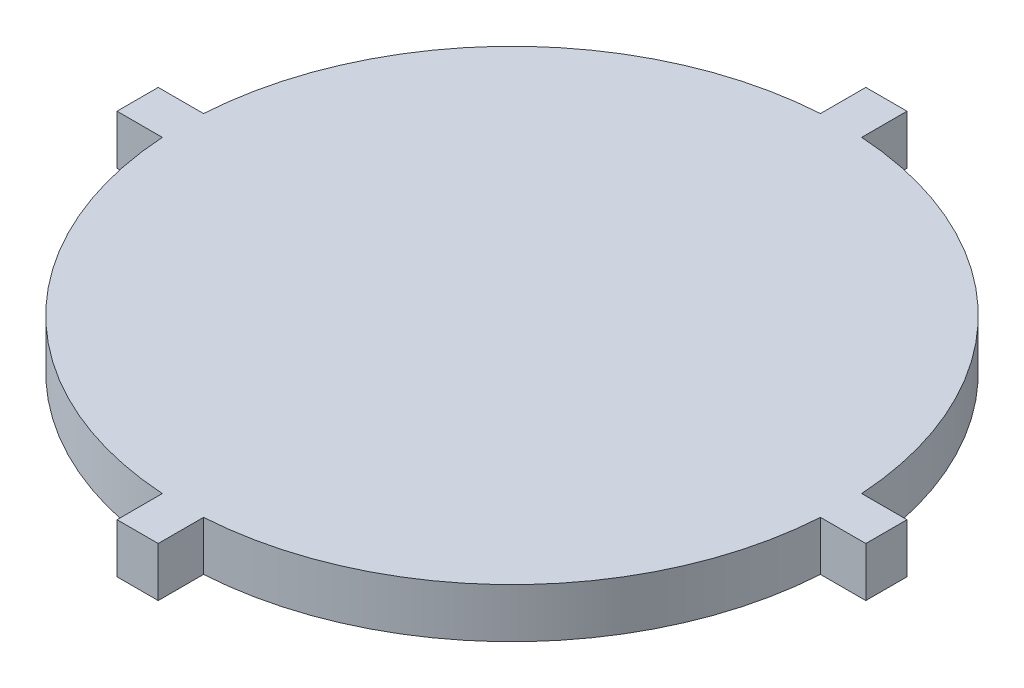
SolidWorks part; units mm, degrees
material "ABS"
ref_plane "Front Plane" through (0, 0, 0) normal (0, 0, 1) x (1, 0, 0)
ref_plane "Top Plane" through (0, 0, 0) normal (0, 1, 0) x (1, 0, 0)
ref_plane "Right Plane" through (0, 0, 0) normal (1, 0, 0) x (0, 0, -1)
other "Bounding Box"
ref_plane "Default Plane" through (-142.8452, 0, 15.5039) normal (0.6267, 0, -0.7793) x (-0.7793, 0, -0.6267)
sketch "Sketch1" plane through (0, 0, 0) normal (0, 1, 0) x (1, 0, 0)
  line L0 (-6.35, 115.3714) -> (6.35, 115.3714)
  line L1 (115.3714, -3.175) -> (115.3714, 6.35)
  line L2 (115.3714, -3.175) -> (115.3714, -6.35)
  line L3 (115.3714, 6.35) -> (101.4014, 6.35)
  line L4 (115.3714, -6.35) -> (101.4014, -6.35)
  line L6 (6.35, 101.4014) -> (6.35, 115.3714)
  line L7 (-6.35, -115.3714) -> (6.35, -115.3714)
  line L8 (-6.35, -101.4014) -> (-6.35, -115.3714)
  line L9 (6.35, -101.4014) -> (6.35, -115.3714)
  line L10 (-6.35, 101.4014) -> (-6.35, 115.3714)
  line L12 (-101.4014, 6.35) -> (-115.3714, 6.35)
  line L13 (-101.4014, -6.35) -> (-115.3714, -6.35)
  line L14 (-115.3714, 6.35) -> (-115.3714, -6.35)
  arc A1 (101.4014, 6.35) -> (6.35, 101.4014) centre (0, 0) ccw
  arc A2 (6.35, -101.4014) -> (101.4014, -6.35) centre (0, 0) ccw
  arc A3 (-101.4014, -6.35) -> (-6.35, -101.4014) centre (0, 0) ccw
  arc A4 (-6.35, 101.4014) -> (-101.4014, 6.35) centre (0, 0) ccw
  dimension "D1" = 12.7
  dimension "D2" = 203.2
  dimension "D3" = 12.7
  dimension "D4" = 13.97
  dimension "D5" = 13.97
  dimension "D6" = 12.7
  dimension "D7" = 13.97
  dimension "D8" = 13.97
  dimension "D9" = 13.97
  dimension "D10" = 13.97
  dimension "D11" = 13.97
  dimension "D12" = 13.97
  dimension "D13" = 12.7
extrude "Boss-Extrude2" add sketch "Sketch1" along normal blind 15.24
